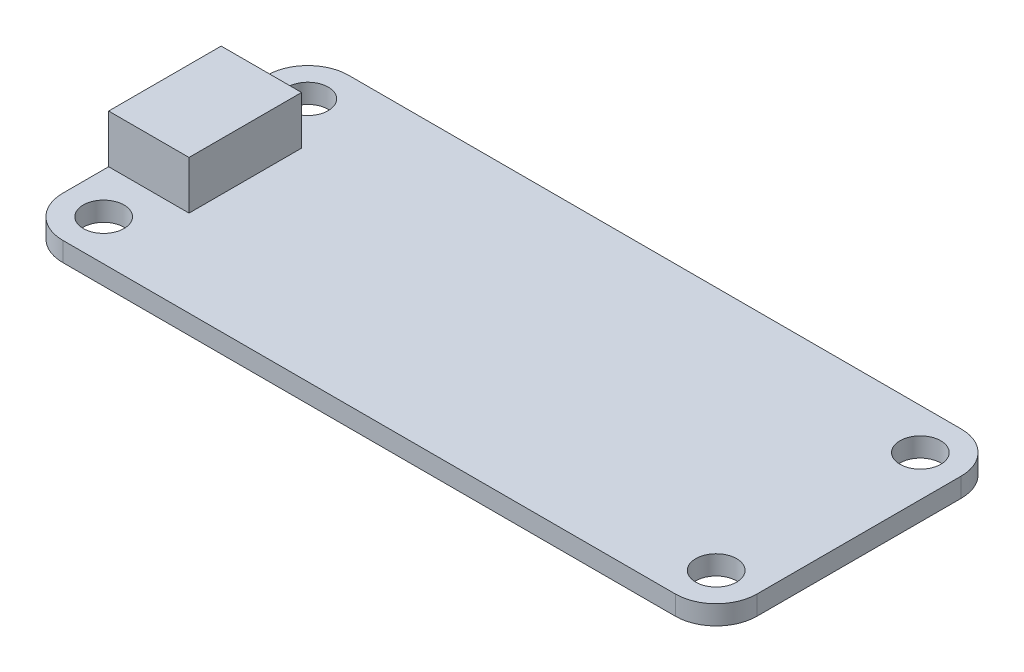
SolidWorks part; units mm, degrees
ref_plane "Front Plane" through (0, 0, 0) normal (0, 0, 1) x (1, 0, 0)
ref_plane "Top Plane" through (0, 0, 0) normal (0, 1, 0) x (1, 0, 0)
ref_plane "Right Plane" through (0, 0, 0) normal (1, 0, 0) x (0, 0, -1)
sketch "Sketch1" plane through (0, 0, 0) normal (0, 1, 0) x (1, 0, 0)
  line L0 (-40.64, 0) -> (-40.64, 2.54) construction
  line L1 (0, 0) -> (-43.18, 0)
  line L2 (0, 0) -> (0, 17.78)
  line L3 (0, 17.78) -> (-43.18, 17.78)
  line L4 (-43.18, 0) -> (-43.18, 17.78)
  line L5 (-40.64, 15.24) -> (-2.54, 15.24) construction
  line L6 (-40.64, 15.24) -> (-40.64, 2.54) construction
  line L7 (-40.64, 2.54) -> (-2.54, 2.54) construction
  line L8 (-2.54, 15.24) -> (-2.54, 2.54) construction
  line L9 (-40.64, 2.54) -> (-43.18, 2.54) construction
  line L10 (0, 15.24) -> (-2.54, 15.24) construction
  line L11 (-2.54, 15.24) -> (-2.54, 17.78) construction
  circle A0 centre (-40.64, 15.24) radius 1.27
  circle A1 centre (-40.64, 2.54) radius 1.27
  circle A2 centre (-2.54, 2.54) radius 1.27
  circle A3 centre (-2.54, 15.24) radius 1.27
  dimension "D3" = 2.54
  dimension "D1" = 43.18
  dimension "D2" = 17.78
  dimension "D4" = 38.1
extrude "Boss-Extrude1" add sketch "Sketch1" along normal blind 1.2
fillet "Fillet1" radius 2.54 4 edges at (-43.18, 0.6, -17.78) (0, 0.6, -17.78) (0, 0.6, 0) (-43.18, 0.6, 0)
sketch "Sketch2" plane through (0, 1.2, 0) normal (0, 1, 0) x (1, 0, 0)
  line L0 (-43.18, 15.24) -> (-43.18, 2.54) construction
  line L1 (-43.18, 5.39) -> (-38.18, 5.39)
  line L2 (-43.18, 5.39) -> (-43.18, 12.39)
  line L3 (-43.18, 12.39) -> (-38.18, 12.39)
  line L4 (-38.18, 5.39) -> (-38.18, 12.39)
  line L5 (-38.18, 12.39) -> (-38.18, 17.78) construction
  line L6 (-2.54, 17.78) -> (-40.64, 17.78) construction
  line L7 (-38.18, 5.39) -> (-38.18, 0) construction
  line L8 (-40.64, 0) -> (-2.54, 0) construction
  dimension "D1" = 7
  dimension "D2" = 5
extrude "Boss-Extrude2" add sketch "Sketch2" along normal blind 3
